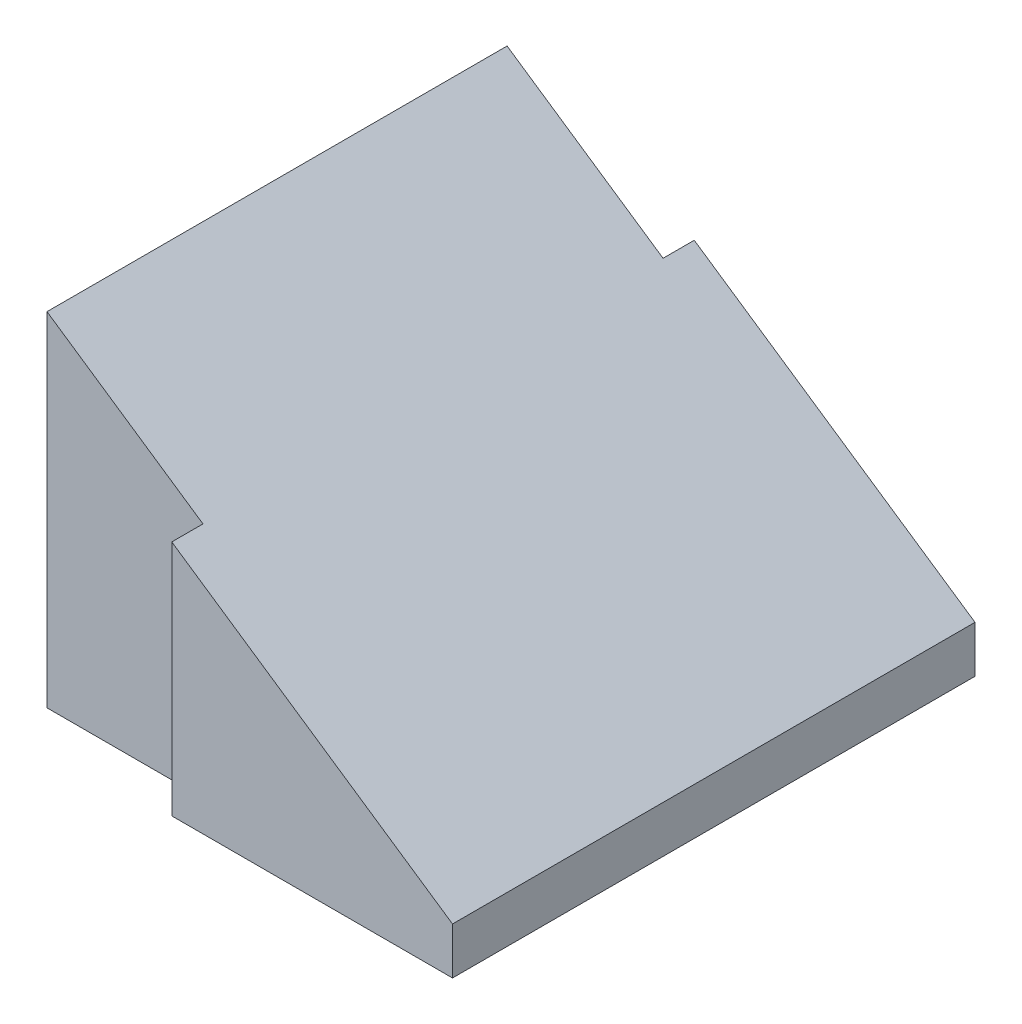
SolidWorks part; units mm, degrees
ref_plane "Front Plane" through (0, 0, 0) normal (0, 0, 1) x (1, 0, 0)
ref_plane "Top Plane" through (0, 0, 0) normal (0, 1, 0) x (1, 0, 0)
ref_plane "Right Plane" through (0, 0, 0) normal (1, 0, 0) x (0, 0, -1)
sketch "Sketch1" plane through (0, 0, 0) normal (0, 1, 0) x (1, 0, 0)
  line L1 (14, -16.75) -> (-14, -16.75)
  line L2 (14, -16.75) -> (14, 16.75)
  line L3 (14, 16.75) -> (-14, 16.75)
  line L4 (-14, -16.75) -> (-14, 16.75)
  line L5 (14, -16.75) -> (-14, 16.75) construction
  line L6 (14, 16.75) -> (-14, -16.75) construction
  point P0 (0, 0)
  dimension "D1" = 33.5
  dimension "D2" = 28
extrude "Boss-Extrude1" add sketch "Sketch1" along normal blind 22
sketch "Sketch3" plane through (0, 0, 16.75) normal (0, 0, 1) x (1, 0, 0)
  line L0 (-14, 22) -> (14, 3)
  line L1 (14, 22) -> (14, 0) construction
  line L3 (-14, 22) -> (14, 22)
  line L4 (-14, 22) -> (-14, 3)
  line L5 (-14, 3) -> (14, 3)
  line L6 (14, 22) -> (14, 3)
  line M6 (14, 0) -> (14, 22)
  line M7 (14, 22) -> (-14, 22)
  dimension "D1" = 3
extrude "Cut-Extrude1" cut sketch "Sketch3" against normal blind 44 contours L0 M7 M6
sketch "Sketch4" plane through (0, 0, 0) normal (0, -1, 0) x (1, 0, 0)
  line L1 (-14, 16.75) -> (14, 16.75)
  line L2 (-14, 16.75) -> (-14, -16.75)
  line L3 (-14, -16.75) -> (14, -16.75)
  line L4 (14, 16.75) -> (14, -16.75)
  line L5 (-14, 14.75) -> (14, 14.75)
  line L6 (-14, 14.75) -> (-14, -14.75)
  line L7 (-14, -14.75) -> (14, -14.75)
  line L8 (14, 14.75) -> (14, -14.75)
  line L9 (-14, 16.75) -> (-4, 16.75)
  line L10 (-14, 16.75) -> (-14, -16.75)
  line L11 (-14, -16.75) -> (-4, -16.75)
  line L12 (-4, 16.75) -> (-4, -16.75)
  line M7 (-14, 16.75) -> (-14, -16.75)
  line M8 (-14, -16.75) -> (14, -16.75)
  dimension "D1" = 2
  dimension "D2" = 2
  dimension "D3" = 10
extrude "Cut-Extrude3" cut sketch "Sketch4" against normal blind 49 contours L12 L1 L5 M7 | L12 L7 M7 M8
